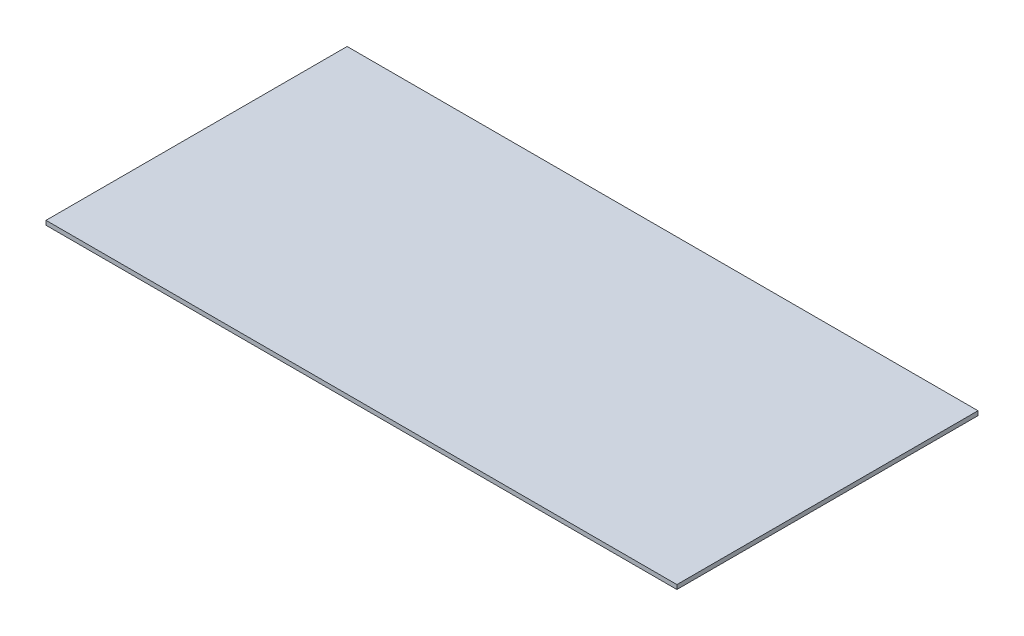
SolidWorks part; units mm, degrees
material "ABS PC"
ref_plane "Front Plane" through (0, 0, 0) normal (0, 0, 1) x (1, 0, 0)
ref_plane "Top Plane" through (0, 0, 0) normal (0, 1, 0) x (1, 0, 0)
ref_plane "Right Plane" through (0, 0, 0) normal (1, 0, 0) x (0, 0, -1)
sketch "Sketch1" plane through (0, 0, 0) normal (0, 1, 0) x (1, 0, 0)
  line L1 (0, 0) -> (880, 0)
  line L2 (0, 0) -> (0, 420)
  line L3 (0, 420) -> (880, 420)
  line L4 (880, 0) -> (880, 420)
  dimension "D1" = 880
  dimension "D2" = 420
extrude "Boss-Extrude1" add sketch "Sketch1" along normal blind 6
